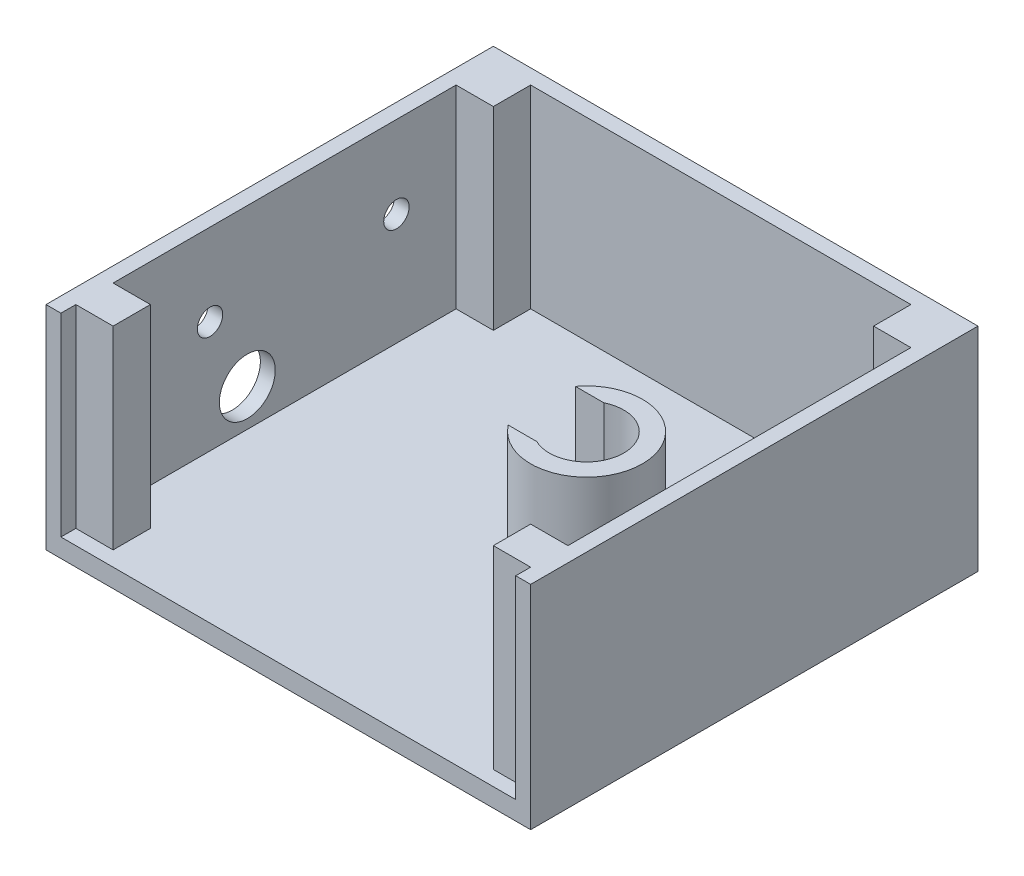
SolidWorks part; units mm, degrees
ref_plane "Front Plane" through (0, 0, 0) normal (0, 0, 1) x (1, 0, 0)
ref_plane "Top Plane" through (0, 0, 0) normal (0, 1, 0) x (1, 0, 0)
ref_plane "Right Plane" through (0, 0, 0) normal (1, 0, 0) x (0, 0, -1)
sketch "Sketch4" plane through (0, 0, 0) normal (0, 1, 0) x (1, 0, 0)
  line L0 (-65, 60) -> (65, 60)
  line L1 (65, 60) -> (65, -60)
  line L2 (65, -60) -> (-65, -60)
  line L3 (-65, -60) -> (-65, 60)
  point P4 (0, 60)
  point P5 (-65, 0)
  dimension "D1" = 120
  dimension "D2" = 130
extrude "Boss-Extrude1" add sketch "Sketch4" along normal blind 5 contours L3 L0 L1 L2
sketch "Sketch5" plane through (0, 5, 0) normal (0, 1, 0) x (1, 0, 0)
  line L0 (-65, -60) -> (-65, 60)
  line L1 (-65, 60) -> (65, 60)
  line L2 (65, 60) -> (65, -60)
  line L3 (65, -60) -> (61, -60)
  line L4 (65, -60) -> (-65, -60) construction
  line L5 (61, -60) -> (61, 56)
  line L6 (61, 56) -> (-61, 56)
  line L7 (-61, 56) -> (-61, -60)
  line L8 (-61, -60) -> (-65, -60)
  dimension "D1" = 4
  dimension "D2" = 4
  dimension "D3" = 4
extrude "Boss-Extrude2" add sketch "Sketch5" along normal blind 52
sketch "Sketch6" plane through (0, 5, 0) normal (0, 1, 0) x (1, 0, 0)
  line L0 (-61, 56) -> (-61, 46)
  line L1 (-61, -60) -> (-61, 56) construction
  line L2 (-61, 46) -> (-51, 46)
  line L3 (-51, 46) -> (-51, 56)
  line L4 (-61, 56) -> (61, 56) construction
  line L5 (-51, 56) -> (-61, 56)
  line L6 (61, 56) -> (51, 56)
  line L7 (-61, 56) -> (61, 56) construction
  line L8 (51, 56) -> (51, 46)
  line L9 (51, 46) -> (61, 46)
  line L10 (61, 56) -> (61, -60) construction
  line L11 (61, 46) -> (61, 56)
  line L12 (61, -56) -> (51, -56)
  line L13 (61, 56) -> (61, -60) construction
  line L14 (51, -56) -> (51, -46)
  line L15 (51, -46) -> (61, -46)
  line L16 (61, -46) -> (61, -56)
  line L17 (-61, -56) -> (-51, -56)
  line L18 (-61, -60) -> (-61, 56) construction
  line L19 (-51, -56) -> (-51, -46)
  line L20 (-51, -46) -> (-61, -46)
  line L21 (-61, -46) -> (-61, -56)
  line L22 (61, -60) -> (-61, -60) construction
  dimension "D1" = 10
  dimension "D2" = 10
  dimension "D3" = 10
  dimension "D4" = 10
  dimension "D5" = 10
  dimension "D6" = 10
  dimension "D7" = 10
  dimension "D8" = 10
  dimension "D9" = 4
extrude "Boss-Extrude3" add sketch "Sketch6" along normal blind 52
sketch "Sketch7" plane through (-65, 0, 0) normal (-1, 0, 0) x (0, 0, 1)
  line L0 (60, 57) -> (60, 0) construction
  line L1 (60, 0) -> (-60, 0) construction
  circle A0 centre (10, 15) radius 7.5
  dimension "D1" = 15
  dimension "D2" = 50
  dimension "D3" = 15
extrude "Cut-Extrude1" cut sketch "Sketch7" against normal blind 5
sketch "Sketch8" plane through (0, 5, 0) normal (0, 1, 0) x (1, 0, 0)
  line L0 (-65, 60) -> (-65, -60) construction
  line L4 (65, 60) -> (-65, 60) construction
  circle A0 centre (15, 5) radius 10
  circle A1 centre (15, 5) radius 15
  dimension "D1" = 20
  dimension "D2" = 30
  dimension "D3" = 80
  dimension "D4" = 55
extrude "Boss-Extrude4" add sketch "Sketch8" along normal blind 30
sketch "Sketch9" plane through (0, 5, 0) normal (0, 1, 0) x (1, 0, 0)
  line L0 (-65, 60) -> (-65, -60) construction
  line L1 (14, -4) -> (14, -5.5901)
  line L2 (14, -5.5901) -> (16, -5.5901)
  line L3 (16, -5.5901) -> (16, -4)
  line L4 (14, 14) -> (14, 15.7615)
  line L5 (14, 15.7615) -> (16, 15.7615)
  line L6 (16, 15.7615) -> (16, 14)
  line L7 (65, 60) -> (-65, 60) construction
  line L8 (61, -60) -> (-61, -60) construction
  arc A0 (14, 14) -> (16, 14) centre (15, 14) ccw
  arc A1 (16, -4) -> (14, -4) centre (15, -4) ccw
  circle A3 centre (15, 5) radius 10 construction
  circle A4 centre (15, 5) radius 10 construction
  dimension "D1" = 2
  dimension "D2" = 2
  dimension "D3" = 80
  dimension "D4" = 44.2385
  dimension "D5" = 54.4099
extrude "Boss-Extrude5" add sketch "Sketch9" along normal blind 10
sketch "Sketch10" plane through (0, 35, 0) normal (0, 1, 0) x (1, 0, 0)
  line L0 (-2, 14) -> (13, 14)
  line L1 (13, 14) -> (13, -4)
  line L2 (13, -4) -> (-2, -4)
  line L3 (-2, -4) -> (-2, 14)
  line L4 (65, 60) -> (-65, 60) construction
  line L5 (65, -60) -> (65, 60) construction
  point P3 (13, 5)
  dimension "D1" = 55
  dimension "D2" = 15
  dimension "D3" = 18
  dimension "D4" = 52
extrude "Cut-Extrude2" cut sketch "Sketch10" against normal blind 30
sketch "Sketch11" plane through (-65, 0, 0) normal (-1, 0, 0) x (0, 0, 1)
  line L0 (-60, 57) -> (-60, 0) construction
  line L1 (60, 0) -> (-60, 0) construction
  circle A0 centre (-30, 35) radius 3.41
  circle A1 centre (20, 35) radius 3.41
  dimension "D1" = 6.82
  dimension "D2" = 6.82
  dimension "D3" = 50
  dimension "D4" = 30
  dimension "D5" = 35
extrude "Cut-Extrude3" cut sketch "Sketch11" against normal blind 5
